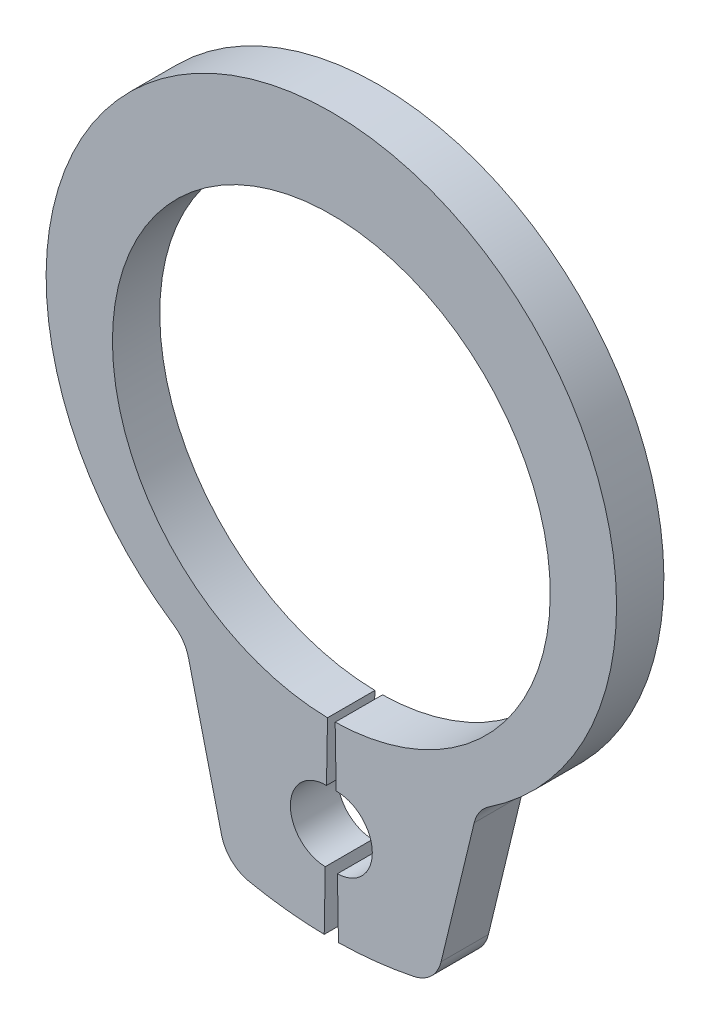
SolidWorks part; units mm, degrees
ref_plane "Front" through (0, 0, 0) normal (0, 0, 1) x (1, 0, 0)
ref_plane "Top" through (0, 0, 0) normal (0, 1, 0) x (1, 0, 0)
ref_plane "Right" through (0, 0, 0) normal (1, 0, 0) x (0, 0, -1)
sketch "Sketch1" plane through (0, 0, 0) normal (0, 0, 1) x (1, 0, 0)
  line L0 (-3.7, 0) -> (3.7, 0) construction
  line L1 (0, 0) -> (0, -3.7) construction
  line L2 (0, -3.7) -> (0, -6.9) construction
  line L3 (0, 0) -> (-0.0646, -3.6994) construction
  line L4 (-0.0646, -3.6994) -> (-0.1204, -6.8989) construction
  line L5 (0.0646, -3.6994) -> (0.1204, -6.8989) construction
  line L6 (0, 0) -> (0.0646, -3.6994) construction
  line L7 (-0.1204, -6.8989) -> (-1.7204, -6.871) construction
  line L8 (-1.7204, -6.871) -> (-2.4716, -3.7604) construction
  line L9 (-2.0322, -3.0919) -> (-2.4716, -3.7604) construction
  line L10 (2.0322, -3.0919) -> (2.4716, -3.7604) construction
  line L11 (-0.0646, -3.6994) -> (-0.082, -4.6993)
  line L12 (-2.4716, -3.7604) -> (-1.7691, -6.6693)
  line L13 (-0.103, -5.8991) -> (-0.1204, -6.8989)
  line L14 (0.0646, -3.6994) -> (0.082, -4.6993)
  line L15 (0.103, -5.8991) -> (0.1204, -6.8989)
  line L16 (2.4716, -3.7604) -> (1.7691, -6.6693)
  circle A0 centre (0, 0) radius 3.7 construction
  circle A1 centre (0, 0.3789) radius 4.8211 construction
  circle A2 centre (0, 0) radius 7.2 construction
  arc A3 (0.0646, -3.6994) -> (-0.0646, -3.6994) centre (0, 0) ccw
  arc A5 (0.1204, -6.8989) -> (1.7691, -6.6693) centre (0, 0) ccw
  circle A6 centre (0.0925, -5.2992) radius 0.6 construction
  arc A7 (0.103, -5.8991) -> (0.082, -4.6993) centre (0.0925, -5.2992) ccw
  arc A8 (2.4716, -3.7604) -> (-2.4716, -3.7604) centre (0, 0.3789) ccw
  arc A9 (-0.103, -5.8991) -> (-0.082, -4.6993) centre (-0.0925, -5.2992) cw
  arc A10 (-1.7691, -6.6693) -> (-0.1204, -6.8989) centre (0, 0) ccw
  point P5 (0, 5.2)
  point P6 (0, 3.7)
  dimension "D6" = 14.4
  dimension "D8" = 1.2
  dimension "D1" = 1.5
  dimension "D2" = 7.4
  dimension "D3" = 1
  dimension "D4" = 3.2
  dimension "D5" = 0.8
  dimension "D7" = 1.6
extrude "Boss-Extrude1" add sketch "Sketch1" along normal mid plane 0.8
fillet "Fillet1" radius 0.6 4 edges at (-1.7691, -6.6693, 0) (-2.4716, -3.7604, 0) (1.7691, -6.6693, 0) (2.4716, -3.7604, 0)
equation "\"D7@Sketch1\"=\"D4@Sketch1\"*.5"
